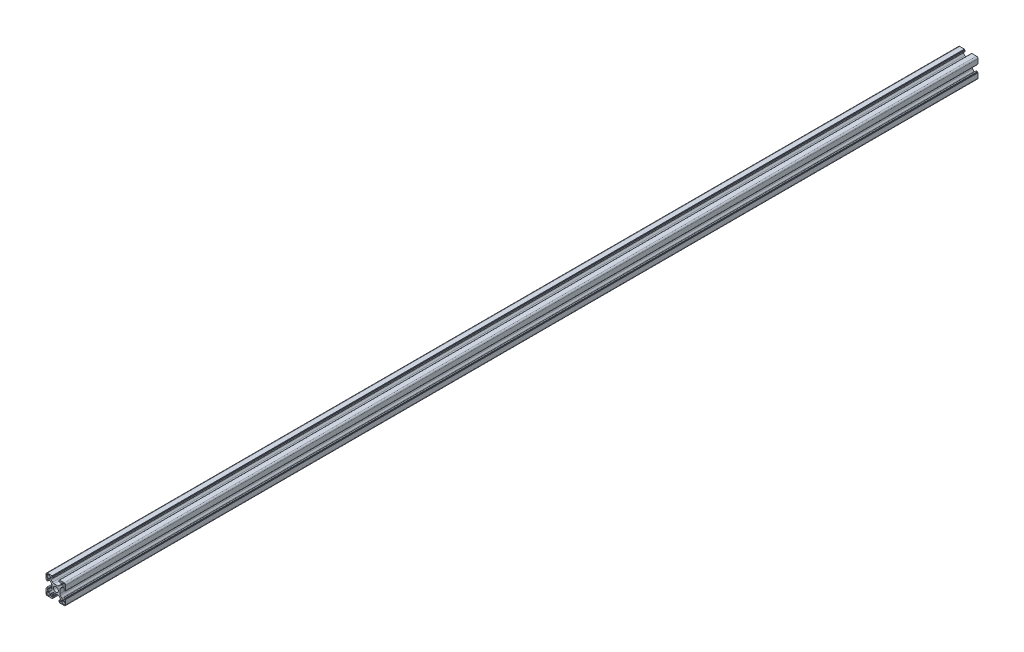
SolidWorks part; units mm, degrees
material "1060 Сплав"
ref_plane "Спереди" through (0, 0, 0) normal (0, 0, 1) x (1, 0, 0)
ref_plane "Сверху" through (0, 0, 0) normal (0, 1, 0) x (1, 0, 0)
ref_plane "Справа" through (0, 0, 0) normal (1, 0, 0) x (0, 0, -1)
sketch "Эскиз2" plane through (0, 0, 0) normal (0, 0, 1) x (1, 0, 0)
  line L0 (9.2299, 9.7837) -> (6.2299, 6.7837) construction
  line L1 (0.1299, 4.6837) -> (2.0286, 4.6837)
  line L2 (0.1299, 0.6837) -> (10.1299, 10.6837) construction
  line L3 (7.7299, 8.2837) -> (6.2299, 9.7837) construction
  line L4 (3.4428, 5.2695) -> (4.7441, 6.5707)
  line L5 (7.0299, 6.7837) -> (8.4299, 6.7837)
  line L6 (6.2299, 7.5837) -> (6.2299, 8.9837)
  line L7 (8.4299, 9.7837) -> (7.0299, 9.7837)
  line L8 (5.3299, 8.8837) -> (5.3299, 7.9849)
  line L9 (3.8931, 8.757) -> (4.3734, 9.2373)
  line L10 (3.3299, 10.2328) -> (3.8299, 10.2328)
  line L11 (3.7163, 8.6837) -> (3.4299, 8.6837)
  line L12 (4.727, 9.3837) -> (4.8299, 9.3837)
  line L13 (3.8299, 10.5337) -> (3.8299, 10.2328)
  line L14 (3.1799, 10.0828) -> (3.1799, 8.9337)
  line L15 (8.6299, 10.6837) -> (3.9799, 10.6837)
  line L16 (9.2299, 8.9837) -> (9.2299, 7.5837)
  line L17 (10.1299, 9.1837) -> (10.1299, 4.5337)
  line L18 (9.5289, 3.7337) -> (8.3799, 3.7337)
  line L19 (9.9799, 4.3837) -> (9.6789, 4.3837)
  line L20 (8.8299, 5.2808) -> (8.8299, 5.3837)
  line L21 (8.1299, 4.2702) -> (8.1299, 3.9837)
  line L22 (9.6789, 3.8837) -> (9.6789, 4.3837)
  line L23 (8.2031, 4.447) -> (8.6834, 4.9273)
  line L24 (8.3299, 5.8837) -> (7.4311, 5.8837)
  line L25 (4.7156, 3.9967) -> (6.0169, 5.2979)
  line L26 (4.1299, 0.6837) -> (4.1299, 2.5825)
  line L27 (4.1299, 0.6837) -> (4.1299, -1.2151)
  line L28 (4.7156, -2.6293) -> (6.0169, -3.9305)
  line L29 (6.2299, -6.2163) -> (6.2299, -7.6163)
  line L30 (7.0299, -5.4163) -> (8.4299, -5.4163)
  line L31 (9.2299, -7.6163) -> (9.2299, -6.2163)
  line L32 (8.3299, -4.5163) -> (7.4311, -4.5163)
  line L33 (8.2031, -3.0795) -> (8.6834, -3.5598)
  line L34 (9.6789, -2.5163) -> (9.6789, -3.0163)
  line L35 (8.1299, -2.9027) -> (8.1299, -2.6163)
  line L36 (8.8299, -3.9134) -> (8.8299, -4.0163)
  line L37 (9.9799, -3.0163) -> (9.6789, -3.0163)
  line L38 (9.5289, -2.3663) -> (8.3799, -2.3663)
  line L39 (10.1299, -7.8163) -> (10.1299, -3.1663)
  line L40 (8.4299, -8.4163) -> (7.0299, -8.4163)
  line L41 (8.6299, -9.3163) -> (3.9799, -9.3163)
  line L42 (3.1799, -8.7153) -> (3.1799, -7.5663)
  line L43 (3.8299, -9.1663) -> (3.8299, -8.8653)
  line L44 (4.727, -8.0163) -> (4.8299, -8.0163)
  line L45 (3.7163, -7.3163) -> (3.4299, -7.3163)
  line L46 (3.3299, -8.8653) -> (3.8299, -8.8653)
  line L47 (3.8931, -7.3895) -> (4.3734, -7.8698)
  line L48 (5.3299, -7.5163) -> (5.3299, -6.6175)
  line L49 (3.4428, -3.9021) -> (4.7441, -5.2033)
  line L50 (0.1299, -3.3163) -> (2.0286, -3.3163)
  line L51 (9.2299, -8.4163) -> (6.2299, -5.4163) construction
  line L52 (0.1299, 0.6837) -> (10.1299, -9.3163) construction
  line L53 (7.7299, -6.9163) -> (9.2299, -5.4163) construction
  line L54 (0.1299, -3.3163) -> (-1.7689, -3.3163)
  line L55 (-3.1831, -3.9021) -> (-4.4844, -5.2033)
  line L56 (-6.7701, -5.4163) -> (-8.1701, -5.4163)
  line L57 (-5.9701, -6.2163) -> (-5.9701, -7.6163)
  line L58 (-8.1701, -8.4163) -> (-6.7701, -8.4163)
  line L59 (-5.0701, -7.5163) -> (-5.0701, -6.6175)
  line L60 (-3.6334, -7.3895) -> (-4.1137, -7.8698)
  line L61 (-3.0701, -8.8653) -> (-3.5701, -8.8653)
  line L62 (-3.4566, -7.3163) -> (-3.1701, -7.3163)
  line L63 (-4.4673, -8.0163) -> (-4.5701, -8.0163)
  line L64 (-3.5701, -9.1663) -> (-3.5701, -8.8653)
  line L65 (-2.9201, -8.7153) -> (-2.9201, -7.5663)
  line L66 (-8.3701, -9.3163) -> (-3.7201, -9.3163)
  line L67 (-8.9701, -7.6163) -> (-8.9701, -6.2163)
  line L68 (-9.8701, -7.8163) -> (-9.8701, -3.1663)
  line L69 (-9.2692, -2.3663) -> (-8.1201, -2.3663)
  line L70 (-9.7201, -3.0163) -> (-9.4192, -3.0163)
  line L71 (-8.5701, -3.9134) -> (-8.5701, -4.0163)
  line L72 (-7.8701, -2.9027) -> (-7.8701, -2.6163)
  line L73 (-9.4192, -2.5163) -> (-9.4192, -3.0163)
  line L74 (-7.9434, -3.0795) -> (-8.4237, -3.5598)
  line L75 (-8.0701, -4.5163) -> (-7.1714, -4.5163)
  line L76 (-4.4559, -2.6293) -> (-5.7572, -3.9305)
  line L77 (-3.8701, 0.6837) -> (-3.8701, -1.2151)
  line L78 (-8.9701, -8.4163) -> (-5.9701, -5.4163) construction
  line L79 (0.1299, 0.6837) -> (-9.8701, -9.3163) construction
  line L80 (-7.4701, -6.9163) -> (-5.9701, -8.4163) construction
  line L81 (-3.8701, 0.6837) -> (-3.8701, 2.5825)
  line L82 (-4.4559, 3.9967) -> (-5.7572, 5.2979)
  line L83 (-5.9701, 7.5837) -> (-5.9701, 8.9837)
  line L84 (-6.7701, 6.7837) -> (-8.1701, 6.7837)
  line L85 (-8.9701, 8.9837) -> (-8.9701, 7.5837)
  line L86 (-8.0701, 5.8837) -> (-7.1714, 5.8837)
  line L87 (-7.9434, 4.447) -> (-8.4237, 4.9273)
  line L88 (-9.4192, 3.8837) -> (-9.4192, 4.3837)
  line L89 (-7.8701, 4.2702) -> (-7.8701, 3.9837)
  line L90 (-8.5701, 5.2808) -> (-8.5701, 5.3837)
  line L91 (-9.7201, 4.3837) -> (-9.4192, 4.3837)
  line L92 (-9.2692, 3.7337) -> (-8.1201, 3.7337)
  line L93 (-9.8701, 9.1837) -> (-9.8701, 4.5337)
  line L94 (-8.1701, 9.7837) -> (-6.7701, 9.7837)
  line L95 (-8.3701, 10.6837) -> (-3.7201, 10.6837)
  line L96 (-2.9201, 10.0828) -> (-2.9201, 8.9337)
  line L97 (-3.5701, 10.5337) -> (-3.5701, 10.2328)
  line L98 (-4.4673, 9.3837) -> (-4.5701, 9.3837)
  line L99 (-3.4566, 8.6837) -> (-3.1701, 8.6837)
  line L100 (-3.0701, 10.2328) -> (-3.5701, 10.2328)
  line L101 (-3.6334, 8.757) -> (-4.1137, 9.2373)
  line L102 (-5.0701, 8.8837) -> (-5.0701, 7.9849)
  line L103 (-3.1831, 5.2695) -> (-4.4844, 6.5707)
  line L104 (0.1299, 4.6837) -> (-1.7689, 4.6837)
  line L105 (-11.6342, 0.6837) -> (11.6342, 0.6837) construction
  line L106 (-8.9701, 9.7837) -> (-5.9701, 6.7837) construction
  line L107 (0.1299, -11.4027) -> (0.1299, 11.4027) construction
  line L108 (0.1299, 0.6837) -> (-9.8701, 10.6837) construction
  line L109 (-7.4701, 8.2837) -> (-8.9701, 6.7837) construction
  arc A0 (9.2299, 8.9837) -> (8.4299, 9.7837) centre (8.4299, 8.9837) ccw
  arc A1 (7.0299, 9.7837) -> (6.2299, 8.9837) centre (7.0299, 8.9837) ccw
  arc A2 (7.0299, 6.7837) -> (6.2299, 7.5837) centre (7.0299, 7.5837) cw
  arc A3 (8.6299, 10.6837) -> (10.1299, 9.1837) centre (8.6299, 9.1837) cw
  arc A4 (3.3299, 10.2328) -> (3.1799, 10.0828) centre (3.3299, 10.0828) ccw
  arc A5 (3.9799, 10.6837) -> (3.8299, 10.5337) centre (3.9799, 10.5337) ccw
  arc A6 (3.7163, 8.6837) -> (3.8931, 8.757) centre (3.7163, 8.9337) ccw
  arc A7 (3.4299, 8.6837) -> (3.1799, 8.9337) centre (3.4299, 8.9337) cw
  arc A8 (4.3734, 9.2373) -> (4.727, 9.3837) centre (4.727, 8.8837) cw
  arc A9 (4.8299, 9.3837) -> (5.3299, 8.8837) centre (4.8299, 8.8837) cw
  arc A10 (2.6299, 0.6837) -> (0.1299, 3.1837) centre (0.1299, 0.6837) ccw
  arc A11 (2.0286, 4.6837) -> (3.4428, 5.2695) centre (2.0286, 6.6837) ccw
  arc A12 (5.3299, 7.9849) -> (4.7441, 6.5707) centre (3.3299, 7.9849) cw
  arc A13 (9.2299, 7.5837) -> (8.4299, 6.7837) centre (8.4299, 7.5837) cw
  arc A14 (8.8299, 5.3837) -> (8.3299, 5.8837) centre (8.3299, 5.3837) ccw
  arc A15 (8.6834, 4.9273) -> (8.8299, 5.2808) centre (8.3299, 5.2808) ccw
  arc A16 (8.1299, 3.9837) -> (8.3799, 3.7337) centre (8.3799, 3.9837) ccw
  arc A17 (8.1299, 4.2702) -> (8.2031, 4.447) centre (8.3799, 4.2702) cw
  arc A18 (10.1299, 4.5337) -> (9.9799, 4.3837) centre (9.9799, 4.5337) cw
  arc A19 (9.6789, 3.8837) -> (9.5289, 3.7337) centre (9.5289, 3.8837) cw
  arc A20 (7.4311, 5.8837) -> (6.0169, 5.2979) centre (7.4311, 3.8837) ccw
  arc A21 (4.1299, 2.5825) -> (4.7156, 3.9967) centre (6.1299, 2.5825) cw
  arc A22 (8.4299, -8.4163) -> (9.2299, -7.6163) centre (8.4299, -7.6163) ccw
  arc A23 (9.2299, -6.2163) -> (8.4299, -5.4163) centre (8.4299, -6.2163) ccw
  arc A24 (6.2299, -6.2163) -> (7.0299, -5.4163) centre (7.0299, -6.2163) cw
  arc A25 (10.1299, -7.8163) -> (8.6299, -9.3163) centre (8.6299, -7.8163) cw
  arc A26 (9.6789, -2.5163) -> (9.5289, -2.3663) centre (9.5289, -2.5163) ccw
  arc A27 (10.1299, -3.1663) -> (9.9799, -3.0163) centre (9.9799, -3.1663) ccw
  arc A28 (8.1299, -2.9027) -> (8.2031, -3.0795) centre (8.3799, -2.9027) ccw
  arc A29 (8.1299, -2.6163) -> (8.3799, -2.3663) centre (8.3799, -2.6163) cw
  arc A30 (8.6834, -3.5598) -> (8.8299, -3.9134) centre (8.3299, -3.9134) cw
  arc A31 (8.8299, -4.0163) -> (8.3299, -4.5163) centre (8.3299, -4.0163) cw
  arc A32 (0.1299, -1.8163) -> (2.6299, 0.6837) centre (0.1299, 0.6837) ccw
  arc A33 (4.1299, -1.2151) -> (4.7156, -2.6293) centre (6.1299, -1.2151) ccw
  arc A34 (7.4311, -4.5163) -> (6.0169, -3.9305) centre (7.4311, -2.5163) cw
  arc A35 (7.0299, -8.4163) -> (6.2299, -7.6163) centre (7.0299, -7.6163) cw
  arc A36 (4.8299, -8.0163) -> (5.3299, -7.5163) centre (4.8299, -7.5163) ccw
  arc A37 (4.3734, -7.8698) -> (4.727, -8.0163) centre (4.727, -7.5163) ccw
  arc A38 (3.4299, -7.3163) -> (3.1799, -7.5663) centre (3.4299, -7.5663) ccw
  arc A39 (3.7163, -7.3163) -> (3.8931, -7.3895) centre (3.7163, -7.5663) cw
  arc A40 (3.9799, -9.3163) -> (3.8299, -9.1663) centre (3.9799, -9.1663) cw
  arc A41 (3.3299, -8.8653) -> (3.1799, -8.7153) centre (3.3299, -8.7153) cw
  arc A42 (5.3299, -6.6175) -> (4.7441, -5.2033) centre (3.3299, -6.6175) ccw
  arc A43 (2.0286, -3.3163) -> (3.4428, -3.9021) centre (2.0286, -5.3163) cw
  arc A44 (-8.9701, -7.6163) -> (-8.1701, -8.4163) centre (-8.1701, -7.6163) ccw
  arc A45 (-6.7701, -8.4163) -> (-5.9701, -7.6163) centre (-6.7701, -7.6163) ccw
  arc A46 (-6.7701, -5.4163) -> (-5.9701, -6.2163) centre (-6.7701, -6.2163) cw
  arc A47 (-8.3701, -9.3163) -> (-9.8701, -7.8163) centre (-8.3701, -7.8163) cw
  arc A48 (-3.0701, -8.8653) -> (-2.9201, -8.7153) centre (-3.0701, -8.7153) ccw
  arc A49 (-3.7201, -9.3163) -> (-3.5701, -9.1663) centre (-3.7201, -9.1663) ccw
  arc A50 (-3.4566, -7.3163) -> (-3.6334, -7.3895) centre (-3.4566, -7.5663) ccw
  arc A51 (-3.1701, -7.3163) -> (-2.9201, -7.5663) centre (-3.1701, -7.5663) cw
  arc A52 (-4.1137, -7.8698) -> (-4.4673, -8.0163) centre (-4.4673, -7.5163) cw
  arc A53 (-4.5701, -8.0163) -> (-5.0701, -7.5163) centre (-4.5701, -7.5163) cw
  arc A54 (-2.3701, 0.6837) -> (0.1299, -1.8163) centre (0.1299, 0.6837) ccw
  arc A55 (-1.7689, -3.3163) -> (-3.1831, -3.9021) centre (-1.7689, -5.3163) ccw
  arc A56 (-5.0701, -6.6175) -> (-4.4844, -5.2033) centre (-3.0701, -6.6175) cw
  arc A57 (-8.9701, -6.2163) -> (-8.1701, -5.4163) centre (-8.1701, -6.2163) cw
  arc A58 (-8.5701, -4.0163) -> (-8.0701, -4.5163) centre (-8.0701, -4.0163) ccw
  arc A59 (-8.4237, -3.5598) -> (-8.5701, -3.9134) centre (-8.0701, -3.9134) ccw
  arc A60 (-7.8701, -2.6163) -> (-8.1201, -2.3663) centre (-8.1201, -2.6163) ccw
  arc A61 (-7.8701, -2.9027) -> (-7.9434, -3.0795) centre (-8.1201, -2.9027) cw
  arc A62 (-9.8701, -3.1663) -> (-9.7201, -3.0163) centre (-9.7201, -3.1663) cw
  arc A63 (-9.4192, -2.5163) -> (-9.2692, -2.3663) centre (-9.2692, -2.5163) cw
  arc A64 (-7.1714, -4.5163) -> (-5.7572, -3.9305) centre (-7.1714, -2.5163) ccw
  arc A65 (-3.8701, -1.2151) -> (-4.4559, -2.6293) centre (-5.8701, -1.2151) cw
  arc A66 (-8.1701, 9.7837) -> (-8.9701, 8.9837) centre (-8.1701, 8.9837) ccw
  arc A67 (-8.9701, 7.5837) -> (-8.1701, 6.7837) centre (-8.1701, 7.5837) ccw
  arc A68 (-5.9701, 7.5837) -> (-6.7701, 6.7837) centre (-6.7701, 7.5837) cw
  arc A69 (-9.8701, 9.1837) -> (-8.3701, 10.6837) centre (-8.3701, 9.1837) cw
  arc A70 (-9.4192, 3.8837) -> (-9.2692, 3.7337) centre (-9.2692, 3.8837) ccw
  arc A71 (-9.8701, 4.5337) -> (-9.7201, 4.3837) centre (-9.7201, 4.5337) ccw
  arc A72 (-7.8701, 4.2702) -> (-7.9434, 4.447) centre (-8.1201, 4.2702) ccw
  arc A73 (-7.8701, 3.9837) -> (-8.1201, 3.7337) centre (-8.1201, 3.9837) cw
  arc A74 (-8.4237, 4.9273) -> (-8.5701, 5.2808) centre (-8.0701, 5.2808) cw
  arc A75 (-8.5701, 5.3837) -> (-8.0701, 5.8837) centre (-8.0701, 5.3837) cw
  arc A76 (0.1299, 3.1837) -> (-2.3701, 0.6837) centre (0.1299, 0.6837) ccw
  arc A77 (-3.8701, 2.5825) -> (-4.4559, 3.9967) centre (-5.8701, 2.5825) ccw
  arc A78 (-7.1714, 5.8837) -> (-5.7572, 5.2979) centre (-7.1714, 3.8837) cw
  arc A79 (-6.7701, 9.7837) -> (-5.9701, 8.9837) centre (-6.7701, 8.9837) cw
  arc A80 (-4.5701, 9.3837) -> (-5.0701, 8.8837) centre (-4.5701, 8.8837) ccw
  arc A81 (-4.1137, 9.2373) -> (-4.4673, 9.3837) centre (-4.4673, 8.8837) ccw
  arc A82 (-3.1701, 8.6837) -> (-2.9201, 8.9337) centre (-3.1701, 8.9337) ccw
  arc A83 (-3.4566, 8.6837) -> (-3.6334, 8.757) centre (-3.4566, 8.9337) cw
  arc A84 (-3.7201, 10.6837) -> (-3.5701, 10.5337) centre (-3.7201, 10.5337) cw
  arc A85 (-3.0701, 10.2328) -> (-2.9201, 10.0828) centre (-3.0701, 10.0828) cw
  arc A86 (-5.0701, 7.9849) -> (-4.4844, 6.5707) centre (-3.0701, 7.9849) ccw
  arc A87 (-1.7689, 4.6837) -> (-3.1831, 5.2695) centre (-1.7689, 6.6837) cw
  point P0 (0.1299, 0.6837)
  point P9 (0.1299, 0.6837)
  point P40 (8.8299, 4.3837)
  point P93 (3.8299, -8.0163)
  point P144 (3.8299, 9.3837)
  point P152 (8.8299, -3.0163)
  point P153 (0.1299, -3.2405)
  point P154 (0.1299, 0.6837)
  point P189 (-8.5701, -3.0163)
  point P228 (-3.5701, -8.0163)
  point P229 (-3.7944, 0.6837)
  point P230 (0.1299, 0.6837)
  point P268 (-3.5701, 9.3837)
  point P273 (4.0541, 0.6837)
  point P306 (-8.5701, 4.3837)
  point P307 (0.1299, 4.608)
  point P309 (0.1299, 0.6837)
  dimension "D3" = 5
  dimension "D6" = 2
  dimension "D1" = 2
  dimension "D2" = 6
  dimension "D4" = 4
  dimension "D5" = 0.9
extrude "Бобышка-Вытянуть1" add sketch "Эскиз2" along normal blind 925
